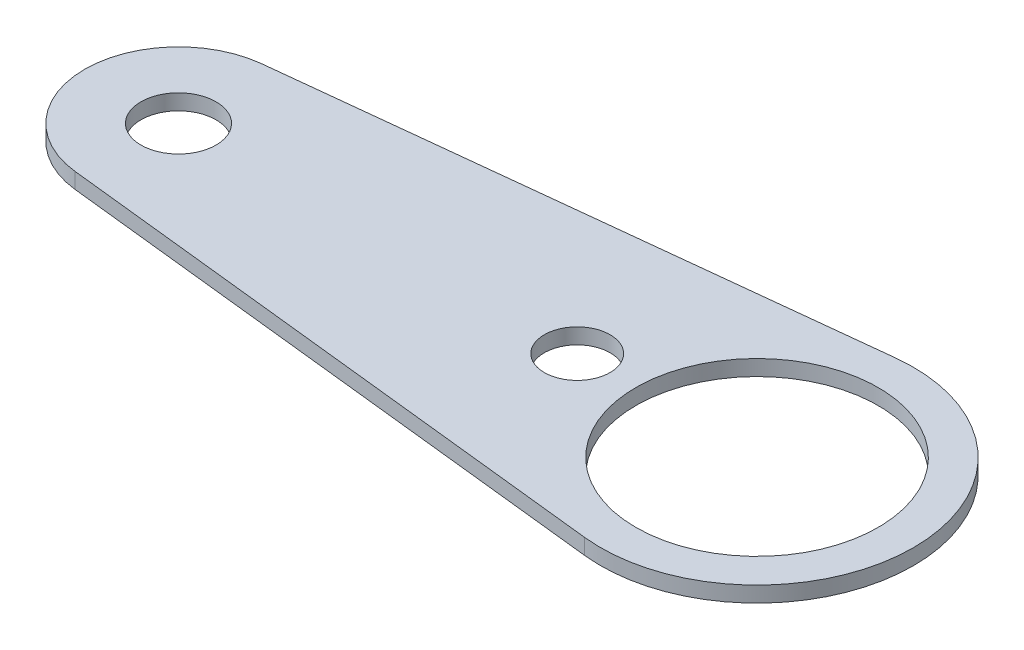
SolidWorks part; units mm, degrees
material "1060 Alloy"
ref_plane "Front Plane" through (0, 0, 0) normal (0, 0, 1) x (1, 0, 0)
ref_plane "Top Plane" through (0, 0, 0) normal (0, 1, 0) x (1, 0, 0)
ref_plane "Right Plane" through (0, 0, 0) normal (1, 0, 0) x (0, 0, -1)
sketch "Sketch1" plane through (0, 0, 0) normal (0, 1, 0) x (1, 0, 0)
  line L0 (-1.0811, 9.9414) -> (-37.6486, 5.9648)
  line L1 (-1.0811, -9.9414) -> (-37.6486, -5.9648)
  arc A0 (-1.0811, -9.9414) -> (-1.0811, 9.9414) centre (0, 0) ccw
  arc A1 (-37.6486, 5.9648) -> (-37.6486, -5.9648) centre (-37, 0) ccw
  circle A2 centre (-37, 0) radius 2.4
  circle A3 centre (0, 0) radius 7.75
  circle A4 centre (-11.5, 0) radius 2.1
  dimension "D1" = 20
  dimension "D2" = 12
  dimension "D3" = 37
  dimension "D4" = 15.5
  dimension "D5" = 4.8
  dimension "D6" = 11.5
  dimension "D7" = 4.2
  dimension "D8" = 10
  dimension "D9" = 15.5
extrude "Boss-Extrude1" add sketch "Sketch1" along normal blind 1
